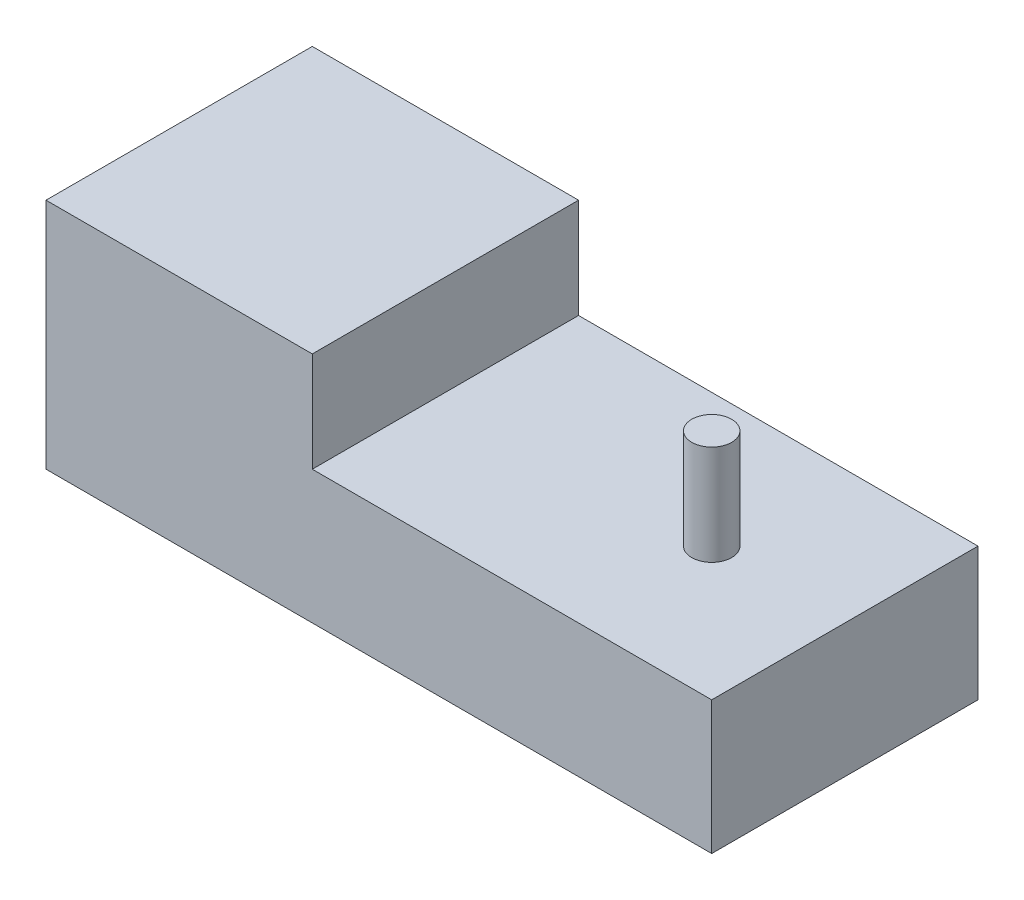
SolidWorks part; units mm, degrees
ref_plane "Front Plane" through (0, 0, 0) normal (0, 0, 1) x (1, 0, 0)
ref_plane "Top Plane" through (0, 0, 0) normal (0, 1, 0) x (1, 0, 0)
ref_plane "Right Plane" through (0, 0, 0) normal (1, 0, 0) x (0, 0, -1)
sketch "Sketch1" plane through (0, 0, 0) normal (0, 1, 0) x (1, 0, 0)
  line L1 (0, 0) -> (100, 0)
  line L2 (0, 0) -> (0, 40)
  line L3 (0, 40) -> (100, 40)
  line L4 (100, 0) -> (100, 40)
  dimension "D1" = 100
  dimension "D2" = 40
extrude "Boss-Extrude1" add sketch "Sketch1" along normal blind 20
sketch "Sketch2" plane through (0, 20, 0) normal (0, 1, 0) x (1, 0, 0)
  line L0 (0, 0) -> (100, 0) construction
  line L1 (100, 0) -> (100, 40) construction
  circle A0 centre (80, 20) radius 3
  dimension "D3" = 6
  dimension "D1" = 20
  dimension "D2" = 20
extrude "Boss-Extrude2" add sketch "Sketch2" along normal blind 15
sketch "Sketch3" plane through (0, 20, 0) normal (0, 1, 0) x (1, 0, 0)
  line L0 (100, 40) -> (0, 40) construction
  line L1 (0, 0) -> (40, 0)
  line L2 (0, 0) -> (0, 40)
  line L3 (0, 40) -> (40, 40)
  line L4 (40, 0) -> (40, 40)
  dimension "D1" = 40
extrude "Boss-Extrude3" add sketch "Sketch3" along normal blind 15
